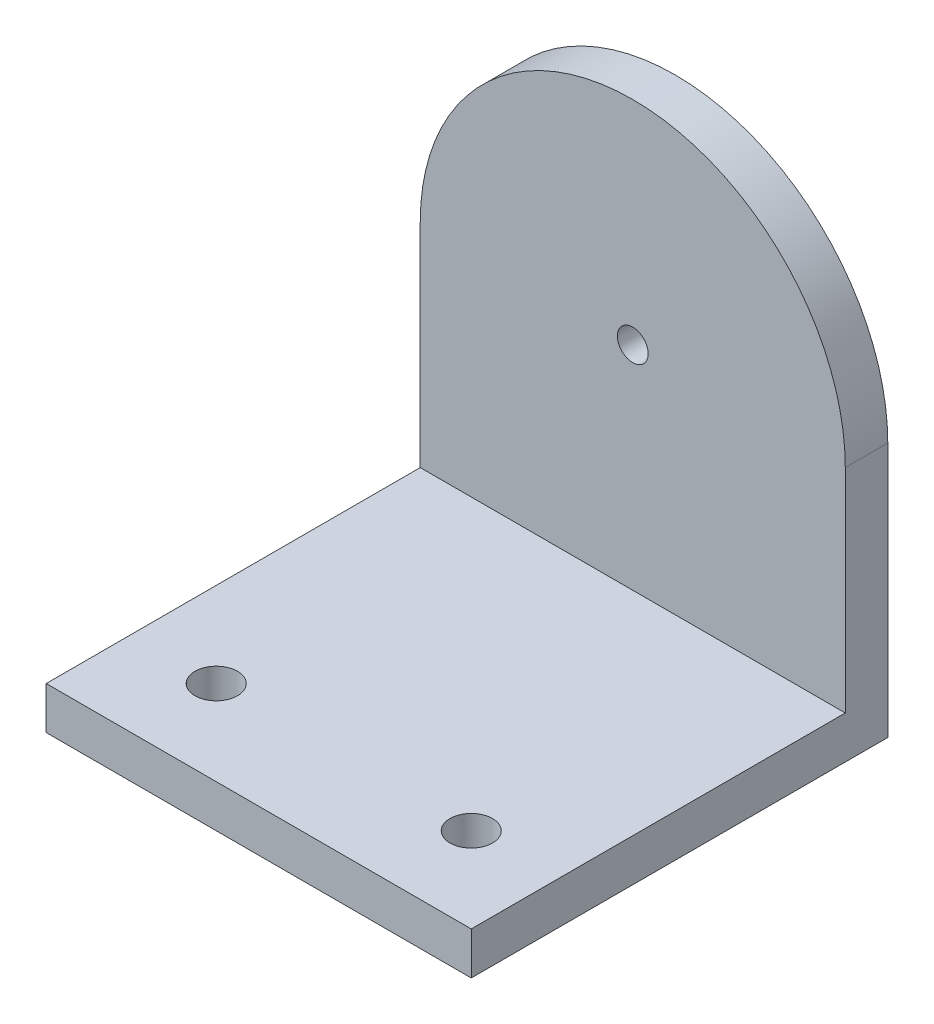
SolidWorks part; units mm, degrees
ref_plane "Front Plane" through (0, 0, 0) normal (0, 0, 1) x (1, 0, 0)
ref_plane "Top Plane" through (0, 0, 0) normal (0, 1, 0) x (1, 0, 0)
ref_plane "Right Plane" through (0, 0, 0) normal (1, 0, 0) x (0, 0, -1)
sketch "Sketch1" plane through (0, 0, 0) normal (0, 0, 1) x (1, 0, 0)
  line L1 (-15.875, 0) -> (15.875, 0)
  line L2 (-15.875, 0) -> (-15.875, -19.05)
  line L3 (-15.875, -19.05) -> (15.875, -19.05)
  line L4 (15.875, 0) -> (15.875, -19.05)
  circle A0 centre (0, 0) radius 15.875
  arc A2 (-15.875, 0) -> (15.875, 0) centre (0, 0) ccw
  dimension "D1" = 31.75
  dimension "D2" = 19.05
extrude "Boss-Extrude1" add sketch "Sketch1" along normal blind 3.175
sketch "Sketch4" plane through (0, 0, 3.175) normal (0, 0, 1) x (1, 0, 0)
  line L0 (15.875, 0) -> (15.875, -19.05) construction
  line L1 (-15.875, -19.05) -> (15.875, -19.05)
  line L2 (-15.875, -19.05) -> (-15.875, -15.875)
  line L3 (-15.875, -15.875) -> (15.875, -15.875)
  line L4 (15.875, -19.05) -> (15.875, -15.875)
  dimension "D1" = 3.175
extrude "Boss-Extrude2" add sketch "Sketch4" along normal blind 27.94
sketch "Sketch5" plane through (0, -15.875, 0) normal (0, 1, 0) x (1, 0, 0)
  line L0 (-15.875, -24.765) -> (15.875, -24.765) construction
  line L2 (-15.875, -31.115) -> (-15.875, -3.175) construction
  line L3 (0, -3.175) -> (0, -31.115) construction
  line L4 (15.875, -3.175) -> (-15.875, -3.175) construction
  line L5 (15.875, -31.115) -> (-15.875, -31.115) construction
  line L6 (15.875, -31.115) -> (15.875, -3.175) construction
  circle A0 centre (-9.525, -24.765) radius 1.5875
  circle A1 centre (9.525, -24.765) radius 1.5875
  point P2 (0, 0)
  point P4 (0, 0)
  point P14 (0, 0)
  dimension "D1" = 3.175
  dimension "D2" = 9.525
  dimension "D3" = 6.35
extrude "Cut-Extrude2" cut sketch "Sketch5" against normal through all
sketch "Sketch6" plane through (0, 0, 3.175) normal (0, 0, 1) x (1, 0, 0)
  circle A0 centre (0, 0) radius 1.15
  dimension "D1" = 2.3
extrude "Cut-Extrude3" cut sketch "Sketch6" against normal through all
